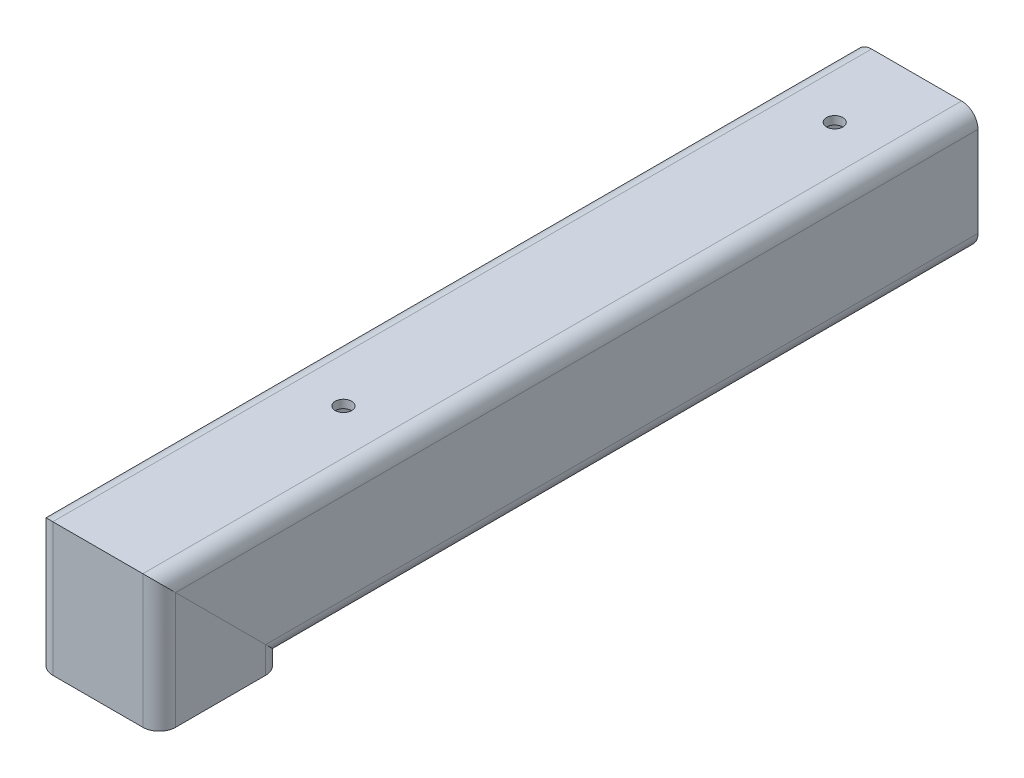
SolidWorks part; units mm, degrees
ref_plane "前视基准面" through (0, 0, 0) normal (0, 0, 1) x (1, 0, 0)
ref_plane "上视基准面" through (0, 0, 0) normal (0, 1, 0) x (1, 0, 0)
ref_plane "右视基准面" through (0, 0, 0) normal (1, 0, 0) x (0, 0, -1)
sketch "草图1" plane through (0, 0, 0) normal (0, 1, 0) x (1, 0, 0)
  line L0 (-11, -13) -> (11, -13)
  line L1 (-11, -15) -> (11, -15)
  line L2 (-15, -11) -> (-15, 11)
  line L3 (-11, 15) -> (11, 15)
  line L4 (15, -11) -> (15, 11)
  line L5 (13, -11) -> (13, 11)
  line L6 (-11, 13) -> (11, 13)
  line L7 (-13, -11) -> (-13, 11)
  arc A0 (-11, -15) -> (-15, -11) centre (-11, -11) cw
  arc A1 (11, -15) -> (15, -11) centre (11, -11) ccw
  arc A2 (11, 15) -> (15, 11) centre (11, 11) cw
  arc A3 (-15, 11) -> (-11, 15) centre (-11, 11) cw
  arc A4 (11, -13) -> (13, -11) centre (11, -11) ccw
  arc A5 (11, 13) -> (13, 11) centre (11, 11) cw
  arc A6 (-13, 11) -> (-11, 13) centre (-11, 11) cw
  arc A7 (-11, -13) -> (-13, -11) centre (-11, -11) cw
extrude "凸台-拉伸1" add sketch "草图1" along normal blind 32.5
sketch "草图2" plane through (0, 0, 0) normal (1, 0, 0) x (0, 0, -1)
  line L0 (-15, 32.5) -> (15, 32.5)
  line L1 (15, 32.5) -> (15, 2.5)
  line L2 (15, 32.5) -> (15, 0) construction
  line L3 (15, 2.5) -> (-15, 32.5)
  dimension "D1" = 45
extrude "切除-拉伸1" cut sketch "草图2" against normal through all both and the other way through all
ref_plane "基准面1" through (0, 0, -185) normal (0, 0, 1) x (1, 0, 0)
sketch "草图3" plane through (0, 0, -185) normal (0, 0, 1) x (1, 0, 0)
  line L0 (-11, 4.5) -> (11, 4.5)
  line L1 (-11, 2.5) -> (11, 2.5)
  line L2 (-15, 6.5) -> (-15, 28.5)
  line L3 (-11, 32.5) -> (11, 32.5)
  line L4 (15, 6.5) -> (15, 28.5)
  line L5 (13, 6.5) -> (13, 28.5)
  line L6 (-11, 30.5) -> (11, 30.5)
  line L7 (-13, 6.5) -> (-13, 28.5)
  arc A0 (-11, 2.5) -> (-15, 6.5) centre (-11, 6.5) cw
  arc A1 (11, 2.5) -> (15, 6.5) centre (11, 6.5) ccw
  arc A2 (11, 32.5) -> (15, 28.5) centre (11, 28.5) cw
  arc A3 (-15, 28.5) -> (-11, 32.5) centre (-11, 28.5) cw
  arc A4 (11, 4.5) -> (13, 6.5) centre (11, 6.5) ccw
  arc A5 (11, 30.5) -> (13, 28.5) centre (11, 28.5) cw
  arc A6 (-13, 28.5) -> (-11, 30.5) centre (-11, 28.5) cw
  arc A7 (-11, 4.5) -> (-13, 6.5) centre (-11, 6.5) cw
  dimension "D1" = 30
  dimension "D2" = 30
  dimension "D3" = 2
  dimension "D4" = 26
  dimension "D5" = 26
  dimension "D6" = 2
extrude "凸台-拉伸2" add sketch "草图3" along normal up to surface (170 mm away) separate body
sketch "草图4" plane through (0, 0, 0) normal (0, 1, 0) x (1, 0, 0)
  line L0 (-12.1, 185) -> (12.1, 185) construction
  circle A0 centre (0, 165) radius 2
  circle A1 centre (0, 45) radius 2
  point P6 (0, 0)
  dimension "D1" = 4
  dimension "D2" = 120
  dimension "D3" = 20
extrude "切除-拉伸2" cut sketch "草图4" along normal through all
